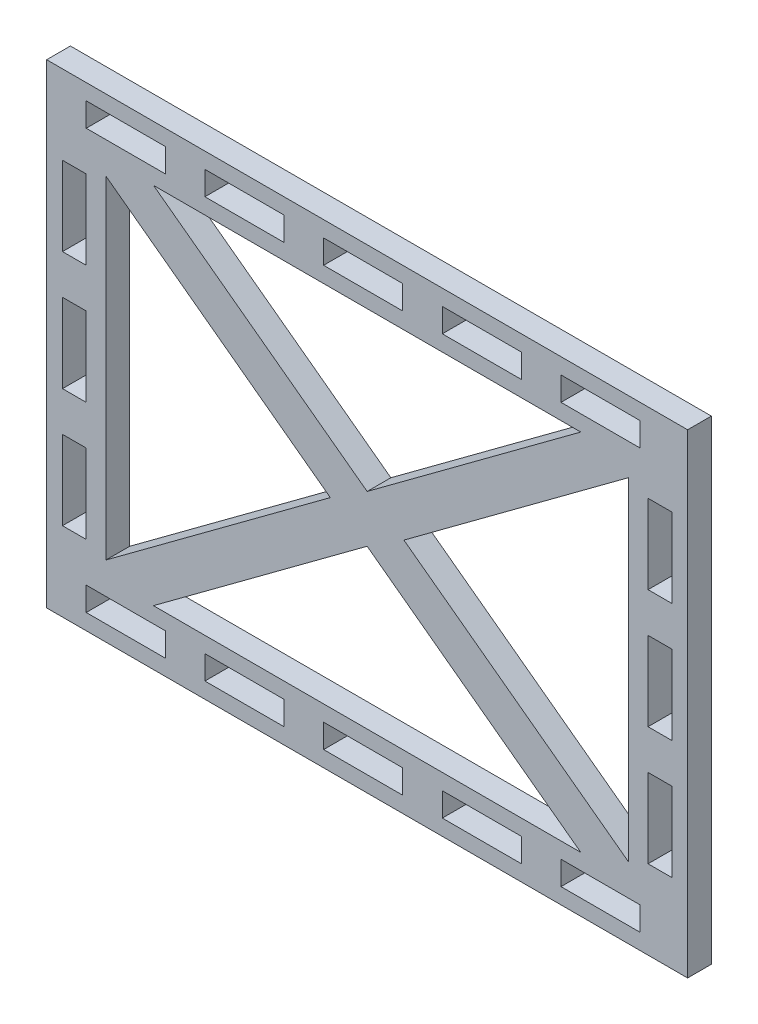
SolidWorks part; units mm, degrees
material "轻木"
ref_plane "前视基准面" through (0, 0, 0) normal (0, 0, 1) x (1, 0, 0)
ref_plane "上视基准面" through (0, 0, 0) normal (0, 1, 0) x (1, 0, 0)
ref_plane "右视基准面" through (0, 0, 0) normal (1, 0, 0) x (0, 0, -1)
sketch "草图1" plane through (0, 0, 0) normal (0, 0, 1) x (1, 0, 0)
  line L1 (-40.5, 30) -> (40.5, 30)
  line L2 (-40.5, 30) -> (-40.5, -30)
  line L3 (-40.5, -30) -> (40.5, -30)
  line L4 (40.5, 30) -> (40.5, -30)
  line L5 (-40.5, 30) -> (40.5, -30) construction
  line L6 (-40.5, -30) -> (40.5, 30) construction
  line L7 (-35.5, 28) -> (-25.5, 28)
  line L8 (-35.5, 28) -> (-35.5, 25)
  line L9 (-35.5, 25) -> (-25.5, 25)
  line L10 (-25.5, 28) -> (-25.5, 25)
  line L11 (-38.5, 20) -> (-35.5, 20)
  line L12 (-38.5, 20) -> (-38.5, 10)
  line L13 (-38.5, 10) -> (-35.5, 10)
  line L14 (-35.5, 20) -> (-35.5, 10)
  line L26 (-38.5, 5) -> (-38.5, -5)
  line L27 (-38.5, 5) -> (-35.5, 5)
  line L28 (-35.5, 5) -> (-35.5, -5)
  line L29 (-38.5, -5) -> (-35.5, -5)
  line L30 (-38.5, -10) -> (-38.5, -20)
  line L31 (-38.5, -10) -> (-35.5, -10)
  line L32 (-35.5, -10) -> (-35.5, -20)
  line L33 (-38.5, -20) -> (-35.5, -20)
  line L34 (0, -55) -> (0, 55) construction
  line L35 (38.5, -10) -> (35.5, -10)
  line L36 (35.5, -10) -> (35.5, -20)
  line L37 (38.5, -20) -> (35.5, -20)
  line L38 (38.5, -10) -> (38.5, -20)
  line L39 (38.5, 5) -> (35.5, 5)
  line L40 (35.5, 5) -> (35.5, -5)
  line L41 (38.5, -5) -> (35.5, -5)
  line L42 (38.5, 5) -> (38.5, -5)
  line L43 (38.5, 10) -> (35.5, 10)
  line L44 (35.5, 20) -> (35.5, 10)
  line L45 (38.5, 20) -> (35.5, 20)
  line L46 (38.5, 20) -> (38.5, 10)
  line L64 (-20.5, 28) -> (-20.5, 25)
  line L65 (-20.5, 28) -> (-10.5, 28)
  line L66 (-10.5, 28) -> (-10.5, 25)
  line L67 (-20.5, 25) -> (-10.5, 25)
  line L68 (-5.5, 28) -> (-5.5, 25)
  line L69 (-5.5, 28) -> (4.5, 28)
  line L70 (4.5, 28) -> (4.5, 25)
  line L71 (-5.5, 25) -> (4.5, 25)
  line L72 (9.5, 28) -> (9.5, 25)
  line L73 (9.5, 28) -> (19.5, 28)
  line L74 (19.5, 28) -> (19.5, 25)
  line L75 (9.5, 25) -> (19.5, 25)
  line L76 (24.5, 28) -> (24.5, 25)
  line L77 (24.5, 28) -> (34.5, 28)
  line L78 (34.5, 28) -> (34.5, 25)
  line L79 (24.5, 25) -> (34.5, 25)
  line L80 (55, 0) -> (-55, 0) construction
  line L81 (24.5, -28) -> (34.5, -28)
  line L82 (34.5, -28) -> (34.5, -25)
  line L83 (24.5, -25) -> (34.5, -25)
  line L84 (24.5, -28) -> (24.5, -25)
  line L85 (9.5, -28) -> (19.5, -28)
  line L86 (19.5, -28) -> (19.5, -25)
  line L87 (9.5, -25) -> (19.5, -25)
  line L88 (9.5, -28) -> (9.5, -25)
  line L89 (-5.5, -28) -> (4.5, -28)
  line L90 (4.5, -28) -> (4.5, -25)
  line L91 (-5.5, -25) -> (4.5, -25)
  line L92 (-5.5, -28) -> (-5.5, -25)
  line L93 (-20.5, -28) -> (-10.5, -28)
  line L94 (-10.5, -28) -> (-10.5, -25)
  line L95 (-20.5, -25) -> (-10.5, -25)
  line L96 (-20.5, -28) -> (-20.5, -25)
  line L97 (-35.5, -25) -> (-25.5, -25)
  line L98 (-25.5, -28) -> (-25.5, -25)
  line L99 (-35.5, -28) -> (-25.5, -28)
  line L100 (-35.5, -28) -> (-35.5, -25)
  point P0 (0, 0)
  dimension "D1" = 81
  dimension "D2" = 60
  dimension "D3" = 10
  dimension "D4" = 3
  dimension "D5" = 5
  dimension "D6" = 10
  dimension "D7" = 3
  dimension "D8" = 2
  dimension "D9" = 10
  dimension "D12" = 2
  dimension "D10" = 3
  dimension "D11" = 5
extrude "凸台-拉伸1" add sketch "草图1" along normal blind 3
sketch "草图2" plane through (0, 0, 3) normal (0, 0, 1) x (1, 0, 0)
  line L0 (-40.5, 30) -> (40.5, -30) construction
  line L1 (40.5, 30) -> (-40.5, -30) construction
  line L4 (-27, 23) -> (27, 23)
  line L5 (27, 23) -> (0, 3)
  line L6 (-27, 23) -> (0, 3)
  line L7 (1.65, 0) -> (-1.65, 0) construction
  line L8 (-27, -23) -> (0, -3)
  line L9 (27, -23) -> (0, -3)
  line L10 (-27, -23) -> (27, -23)
  line L12 (33, 21) -> (33, -21)
  line L13 (33, -21) -> (4.65, 0)
  line L14 (33, 21) -> (4.65, 0)
  line L15 (-33, 21) -> (-4.65, 0)
  line L16 (-33, -21) -> (-4.65, 0)
  line L17 (-33, 21) -> (-33, -21)
extrude "切除-拉伸1" cut sketch "草图2" against normal blind 10
